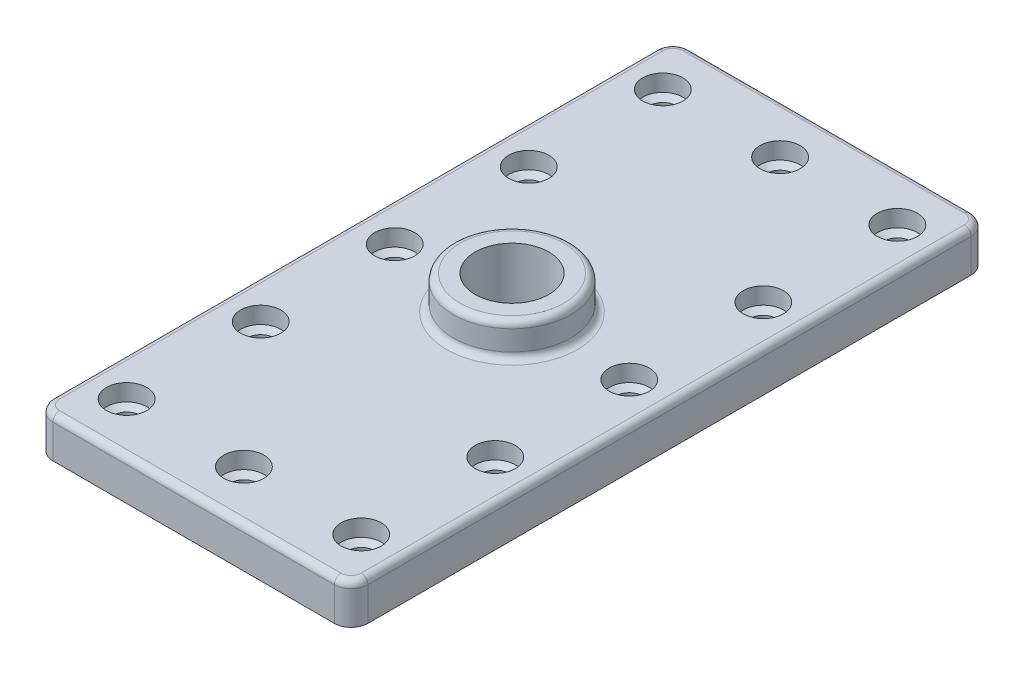
SolidWorks part; units mm, degrees
ref_plane "Front" through (0, 0, 0) normal (0, 0, 1) x (1, 0, 0)
ref_plane "Top" through (0, 0, 0) normal (0, 1, 0) x (1, 0, 0)
ref_plane "Right" through (0, 0, 0) normal (1, 0, 0) x (0, 0, -1)
sketch "Sketch1" plane through (0, 0, 0) normal (0, 1, 0) x (1, 0, 0)
  line L0 (-47, 95) -> (47, -95) construction
  line L1 (-47, -95) -> (47, -95)
  line L2 (-47, -95) -> (-47, 95)
  line L3 (-47, 95) -> (47, 95)
  line L4 (47, -95) -> (47, 95)
  dimension "D1" = 190
  dimension "D2" = 94
extrude "plate" add sketch "Sketch1" along normal blind 12
sketch "Sketch2" plane through (0, 12, 0) normal (0, 1, 0) x (-1, 0, 0)
  circle A0 centre (0, 0) radius 17.5
  dimension "D1" = 35
extrude "boss" add sketch "Sketch2" along normal blind 10
sketch "Sketch3" plane through (0, 22, 0) normal (0, 1, 0) x (-1, 0, 0)
  circle A0 centre (0, 0) radius 11
  dimension "D1" = 22
extrude "center hole" cut sketch "Sketch3" against normal through all
hole_wizard "pattern hole" positions "Sketch5" profile "Sketch4" legacy end condition through all
sketch "Sketch5" plane through (0, 12, 0) normal (0, 1, 0) x (-1, 0, 0)
  line L0 (47, 95) -> (-47, 95) construction
  line L1 (47, -95) -> (47, 95) construction
  point P0 (35, 80)
  dimension "D1" = 15
  dimension "D2" = 12
sketch "Sketch4" plane through (-35, 12, 80) normal (1, 0, 0) x (0, 0, 1)
  line L0 (0, 0) -> (0, 12)
  line L1 (0, 12) -> (4, 12)
  line L2 (4, 12) -> (4, 6.2017)
  line L3 (4, 6.2017) -> (6, 5)
  line L4 (6, 5) -> (6, 0)
  line L5 (6, 0) -> (0, 0)
  line L6 (0, -6.13) -> (0, 109.2824) construction
  line L7 (-4, 6.2017) -> (-6, 5) construction
  line L8 (0, 12) -> (-4, 12) construction
  dimension "Diameter" = 8
  dimension "Depth" = 12
  dimension "C-Drill Diameter" = 12
  dimension "C-Drill Depth" = 5
  dimension "C-Drill Angle" = 118
fillet "R5" radius 5 4 edges at (-47, 6, -95) (47, 6, -95) (47, 6, 95) (-47, 6, 95)
fillet "R2" radius 2 10 edges at (0, 12, -17.5) (0, 22, 17.5) (47, 12, 0) (0, 12, 95) (-47, 12, 0) (0, 12, -95) (45.5355, 12, -93.5355) (-45.5355, 12, -93.5355) (-45.5355, 12, 93.5355) (45.5355, 12, 93.5355)
pattern_linear "LPattern1" count 3 spacing 35 along (1, 0, 0) count 5 spacing 40 along (0, 0, -1) skipping (1, 1), (1, 2), (1, 3) of "pattern hole"
